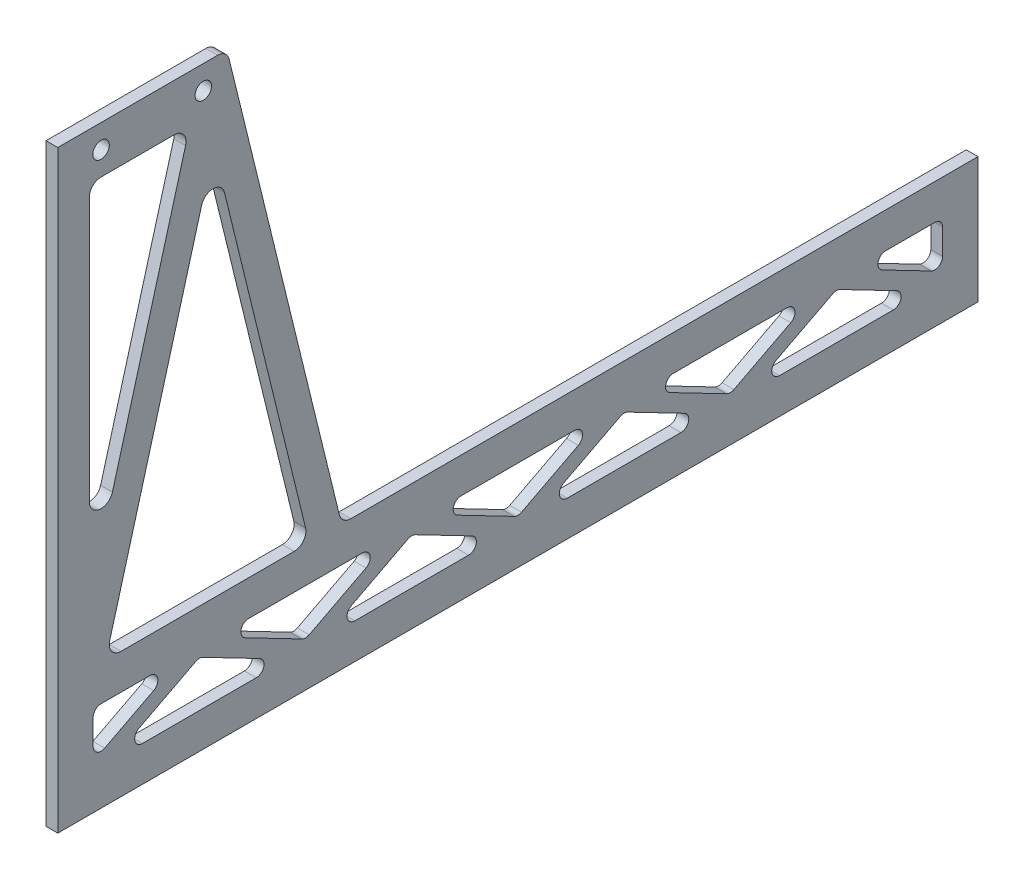
SolidWorks part; units mm, degrees
material "Thornel Mat VMA"
ref_plane "Front Plane" through (0, 0, 0) normal (0, 0, 1) x (1, 0, 0)
ref_plane "Top Plane" through (0, 0, 0) normal (0, 1, 0) x (1, 0, 0)
ref_plane "Right Plane" through (0, 0, 0) normal (1, 0, 0) x (0, 0, -1)
sketch "Sketch1" plane through (0, 0, 0) normal (1, 0, 0) x (0, 0, -1)
  line L0 (0, 0) -> (0, 75.5)
  line L2 (21.5, 75.5) -> (40, 0)
  line L3 (40, 0) -> (35.8817, 0)
  line L4 (35.8817, 0) -> (29.7558, 25)
  line L5 (29.7558, 25) -> (4, 25)
  line L6 (4, 25) -> (4, 0)
  line L7 (4, 0) -> (0, 0)
  line L8 (4, 69.5) -> (18.8519, 69.5)
  line L9 (18.8519, 69.5) -> (4, 29)
  line L10 (4, 29) -> (4, 69.5)
  line L11 (8.2605, 29) -> (20.5584, 62.5355)
  line L12 (20.5584, 62.5355) -> (28.7757, 29)
  line L13 (28.7757, 29) -> (8.2605, 29)
  line L15 (21.5, 75.5) -> (0, 75.5)
  circle A0 centre (5.5, 72.5) radius 1.05
  circle A1 centre (18.5, 72.5) radius 1.05
  dimension "D4" = 2.1
  dimension "D1" = 4
  dimension "D2" = 4
  dimension "D3" = 25
  dimension "D5" = 72.5
  dimension "D6" = 40
  dimension "D8" = 13
  dimension "D9" = 5.5
  dimension "D10" = 3
  dimension "D11" = 4
  dimension "D12" = 3
  dimension "D13" = 4
  dimension "D7" = 3
extrude "Boss-Extrude1" add sketch "Sketch1" along normal blind 1.5
fillet "Fillet1" radius 1.5 9 edges at (0.75, 29, -4) (0.75, 29, -8.2605) (0.75, 25, -29.7558) (0.75, 25, -4) (0.75, 69.5, -4) (0.75, 69.5, -18.8519) (0.75, 62.5355, -20.5584) (0.75, 29, -28.7757) (0.75, 75.5, -21.5)
sketch "Sketch2" plane through (1.5, 0, 0) normal (1, 0, 0) x (0, 0, -1)
  line L1 (0, 0) -> (117, 0)
  line L2 (0, 0) -> (0, 16)
  line L3 (0, 16) -> (117, 16)
  line L4 (117, 0) -> (117, 16)
  dimension "D1" = 117
  dimension "D2" = 16
extrude "Boss-Extrude2" add sketch "Sketch2" against normal up to surface (1.5 mm away) up to face at (0, 72.5, -6.55)
sketch "Sketch5" plane through (1.5, 0, 0) normal (1, 0, 0) x (0, 0, -1)
  line L0 (4.5, 11.5) -> (15.8276, 11.5)
  line L2 (4.5, 11.5) -> (4.5, 5.6264)
  line L4 (112.5, 11.5) -> (112.5, 5.6264)
  line L6 (117, 0) -> (117, 16) construction
  line L7 (0, 75.5) -> (0, 0) construction
  line L10 (6.6724, 4.5) -> (29.3276, 4.5)
  line L11 (33.6724, 4.5) -> (56.3276, 4.5)
  line L12 (60.6724, 4.5) -> (83.3276, 4.5)
  line L13 (87.6724, 4.5) -> (110.3276, 4.5)
  line L15 (20.1724, 11.5) -> (42.8276, 11.5)
  line L18 (47.1724, 11.5) -> (69.8276, 11.5)
  line L19 (101.1724, 11.5) -> (112.5, 11.5)
  line L23 (87.6724, 4.5) -> (99, 10.3736)
  line L24 (99, 10.3736) -> (110.3276, 4.5)
  line L25 (60.6724, 4.5) -> (72, 10.3736)
  line L26 (72, 10.3736) -> (83.3276, 4.5)
  line L27 (33.6724, 4.5) -> (45, 10.3736)
  line L28 (45, 10.3736) -> (56.3276, 4.5)
  line L29 (6.6724, 4.5) -> (18, 10.3736)
  line L30 (18, 10.3736) -> (29.3276, 4.5)
  line L31 (85.5, 5.6264) -> (96.8276, 11.5)
  line L32 (101.1724, 11.5) -> (112.5, 5.6264)
  line L33 (58.5, 5.6264) -> (69.8276, 11.5)
  line L34 (74.1724, 11.5) -> (85.5, 5.6264)
  line L35 (31.5, 5.6264) -> (42.8276, 11.5)
  line L36 (47.1724, 11.5) -> (58.5, 5.6264)
  line L37 (4.5, 5.6264) -> (15.8276, 11.5)
  line L38 (20.1724, 11.5) -> (31.5, 5.6264)
  line L39 (74.1724, 11.5) -> (96.8276, 11.5)
  point P4 (31.5, 11.5)
  point P6 (31.5, 4.5)
  point P7 (85.5, 11.5)
  point P13 (58.5, 4.5)
  point P14 (4.5, 11.5)
  point P15 (112.5, 4.5)
  point P16 (4.5, 4.5)
  point P17 (85.5, 4.5)
  point P21 (58.5, 11.5)
  dimension "D3" = 4.5
  dimension "D4" = 4.5
extrude "Cut-Extrude2" cut sketch "Sketch5" against normal through all contours L37 L0 L2 | L29 L30 L10 | L35 L15 L38 | L27 L28 L11 | L33 L18 L36 | L25 L26 L12 | L31 L39 L34 | L23 L24 L13 | L19 L4 L32
fillet "Fillet3" radius 1 27 edges at (0.75, 5.6264, -112.5) (0.75, 11.5, -47.1724) (0.75, 11.5, -74.1724) (0.75, 11.5, -101.1724) (0.75, 11.5, -112.5) (0.75, 11.5, -96.8276) (0.75, 11.5, -69.8276) (0.75, 5.6264, -85.5) (0.75, 4.5, -60.6724) (0.75, 4.5, -87.6724) (0.75, 5.6264, -58.5) (0.75, 10.3736, -99) (0.75, 10.3736, -72) (0.75, 4.5, -110.3276) (0.75, 4.5, -83.3276) (0.75, 4.5, -56.3276) (0.75, 4.5, -33.6724) (0.75, 10.3736, -45) (0.75, 11.5, -42.8276) (0.75, 11.5, -20.1724) (0.75, 5.6264, -31.5) (0.75, 4.5, -29.3276) (0.75, 10.3736, -18) (0.75, 4.5, -6.6724) (0.75, 5.6264, -4.5) (0.75, 11.5, -15.8276) (0.75, 11.5, -4.5)
sketch "Sketch6" plane through (1.5, 0, 0) normal (1, 0, 0) x (0, 0, -1)
  line L0 (30.9985, 19.9285) -> (18.8519, 69.5)
  line L4 (18.8519, 69.5) -> (4, 69.5)
  line L5 (4, 69.5) -> (4, 19.75)
  line L6 (4, 16) -> (4, 23.5) construction
  line L7 (4, 19.75) -> (30.9985, 19.9285)
  line L8 (30.0359, 23.857) -> (31.9611, 16) construction
extrude "Cut-Extrude3" cut sketch "Sketch6" against normal through all
sketch "Sketch7" plane through (1.5, 0, 0) normal (1, 0, 0) x (0, 0, -1)
  line L1 (16.7762, 69.5) -> (4, 23.4769)
  line L2 (19.825, 65.5285) -> (6.0756, 16)
  line L17 (4, 69.5) -> (4, 16)
  line L18 (4, 16) -> (31.9611, 16)
  line L19 (31.9611, 16) -> (18.8519, 69.5)
  line L20 (18.8519, 69.5) -> (4, 69.5)
  line L21 (4, 23.4769) -> (4, 16)
  line L22 (4, 16) -> (6.0756, 16)
  line L23 (19.825, 65.5285) -> (18.8519, 69.5)
  line L24 (18.8519, 69.5) -> (16.7762, 69.5)
  dimension "D3" = 0
extrude "Boss-Extrude3" add sketch "Sketch7" against normal up to surface (1.5 mm away) up to face at (0, 42.75, -14.7033)
fillet "Fillet5" radius 1.5 7 edges at (0.75, 23.4769, -4) (0.75, 69.5, -16.7762) (0.75, 69.5, -4) (0.75, 65.5285, -19.825) (0.75, 16, -31.9611) (0.75, 16, -6.0756) (0.75, 16, -36.0795)
equation "\"D2@Sketch1\"=\"D1@Sketch1\""
equation "\"D10@Sketch1\"=\"D7@Sketch1\""
equation "\"D11@Sketch1\"=\"D1@Sketch1\""
equation "\"D12@Sketch1\"=\"D7@Sketch1\""
equation "\"D13@Sketch1\"=\"D1@Sketch1\""
